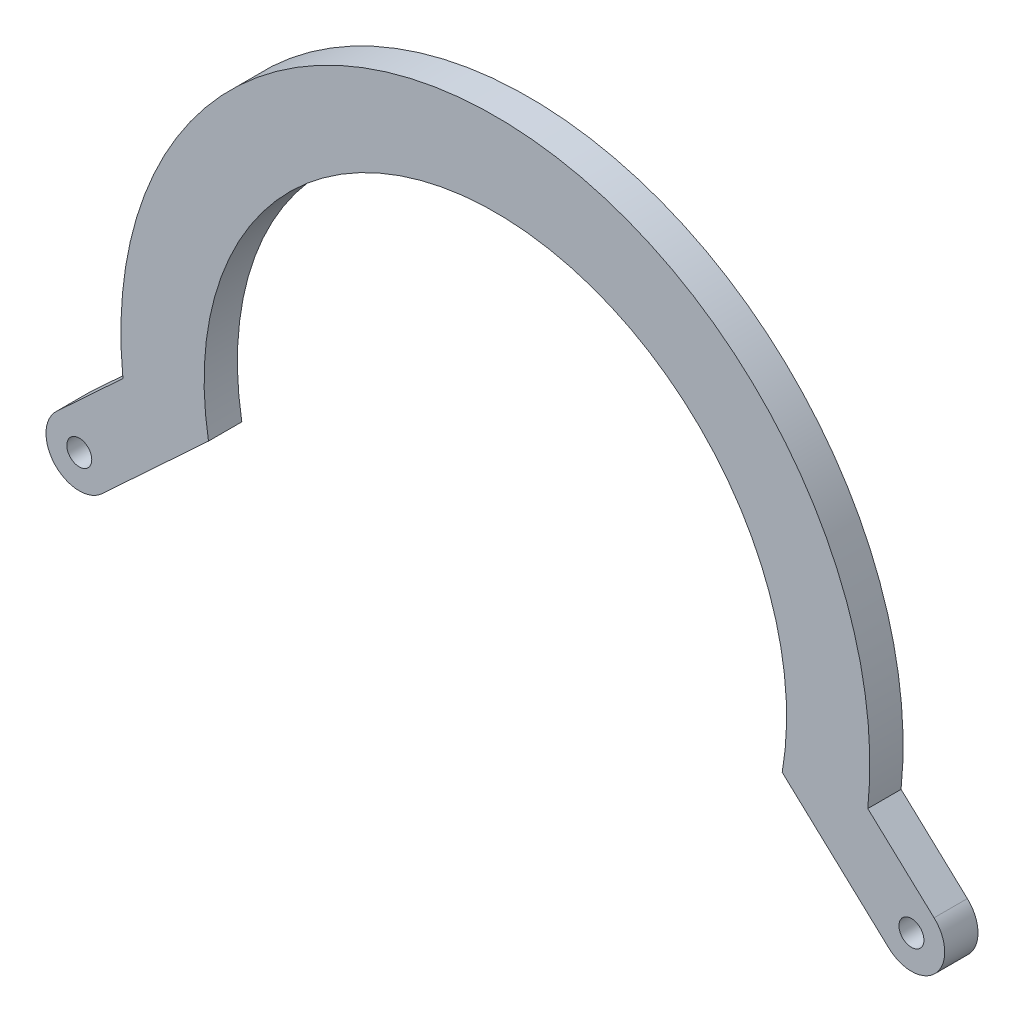
SolidWorks part; units mm, degrees
material "Thornel Mat VMA"
ref_plane "前视基准面" through (0, 0, 0) normal (0, 0, 1) x (1, 0, 0)
ref_plane "上视基准面" through (0, 0, 0) normal (0, 1, 0) x (1, 0, 0)
ref_plane "右视基准面" through (0, 0, 0) normal (1, 0, 0) x (0, 0, -1)
other "Configuration Table"
sketch "草图1" plane through (0, 0, 0) normal (0, 0, 1) x (1, 0, 0)
  line L0 (-50, -15) -> (-31.9695, 1.7198) construction
  line L1 (-52.7198, -12.067) -> (-44.7558, -4.6819)
  line L2 (-47.2802, -17.933) -> (-34.4721, -6.056)
  line L3 (0, 0) -> (0, -12.6277) construction
  line L4 (50, -15) -> (31.9695, 1.7198) construction
  line L5 (47.2802, -17.933) -> (34.4721, -6.056)
  line L6 (52.7198, -12.067) -> (44.7558, -4.6819)
  arc A0 (34.4721, -6.056) -> (-34.4721, -6.056) centre (0, 0) ccw
  circle A2 centre (-50, -15) radius 1.5
  circle A3 centre (50, -15) radius 1.5
  arc A4 (-52.7198, -12.067) -> (-47.2802, -17.933) centre (-50, -15) ccw
  arc A6 (47.2802, -17.933) -> (52.7198, -12.067) centre (50, -15) ccw
  arc A8 (44.7558, -4.6819) -> (-44.7558, -4.6819) centre (0, 0) ccw
  point P8 (-40.9848, -6.6401)
  point P14 (40.9848, -6.6401)
  dimension "D1" = 70
  dimension "D5" = 3
  dimension "D6" = 3
  dimension "D9" = 4
  dimension "D11" = 4
  dimension "D3" = 50
  dimension "D4" = 15
  dimension "D7" = 50
  dimension "D8" = 15
  dimension "D10" = 47.16
  dimension "D12" = 47.16
extrude "凸台-拉伸1" add sketch "草图1" along normal blind 4
